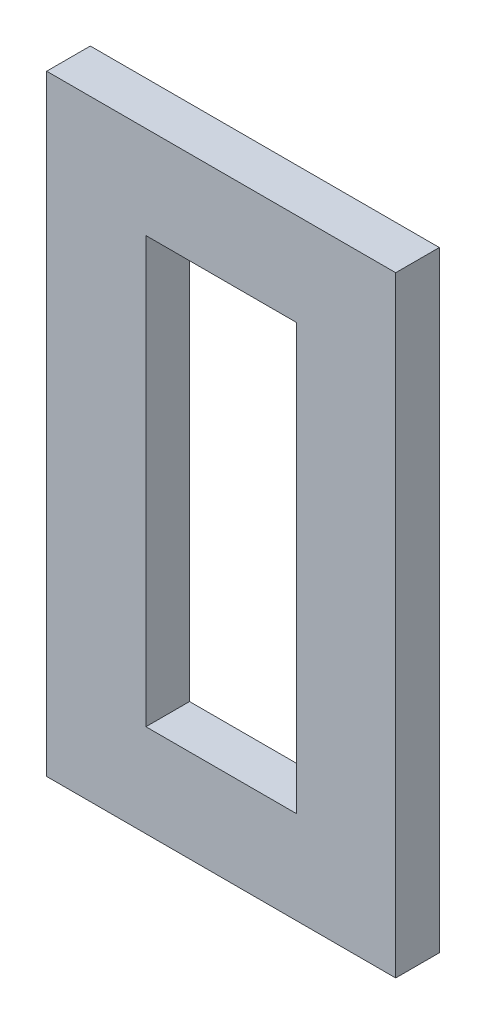
SolidWorks part; units mm, degrees
ref_plane "Front Plane" through (0, 0, 0) normal (0, 0, 1) x (1, 0, 0)
ref_plane "Top Plane" through (0, 0, 0) normal (0, 1, 0) x (1, 0, 0)
ref_plane "Right Plane" through (0, 0, 0) normal (1, 0, 0) x (0, 0, -1)
sketch "Sketch1" plane through (0, 0, 0) normal (0, 0, 1) x (1, 0, 0)
  line L0 (-291.828, 140) -> (-131.828, 140)
  line L1 (-131.828, 140) -> (-131.828, -140)
  line L2 (-131.828, -140) -> (-291.828, -140)
  line L3 (-291.828, -140) -> (-291.828, 140)
  line L7 (-246.328, 97.5) -> (-177.328, 97.5)
  line L8 (-246.328, 97.5) -> (-246.328, -97.5)
  line L9 (-246.328, -97.5) -> (-177.328, -97.5)
  line L10 (-177.328, 97.5) -> (-177.328, -97.5)
  line L11 (-246.328, 97.5) -> (-177.328, -97.5) construction
  line L12 (-246.328, -97.5) -> (-177.328, 97.5) construction
  point P9 (-211.828, 0)
  dimension "D1" = 160
  dimension "D2" = 280
  dimension "D4" = 69
  dimension "D5" = 195
  dimension "D6" = 80
extrude "Boss-Extrude1" add sketch "Sketch1" along normal blind 20
